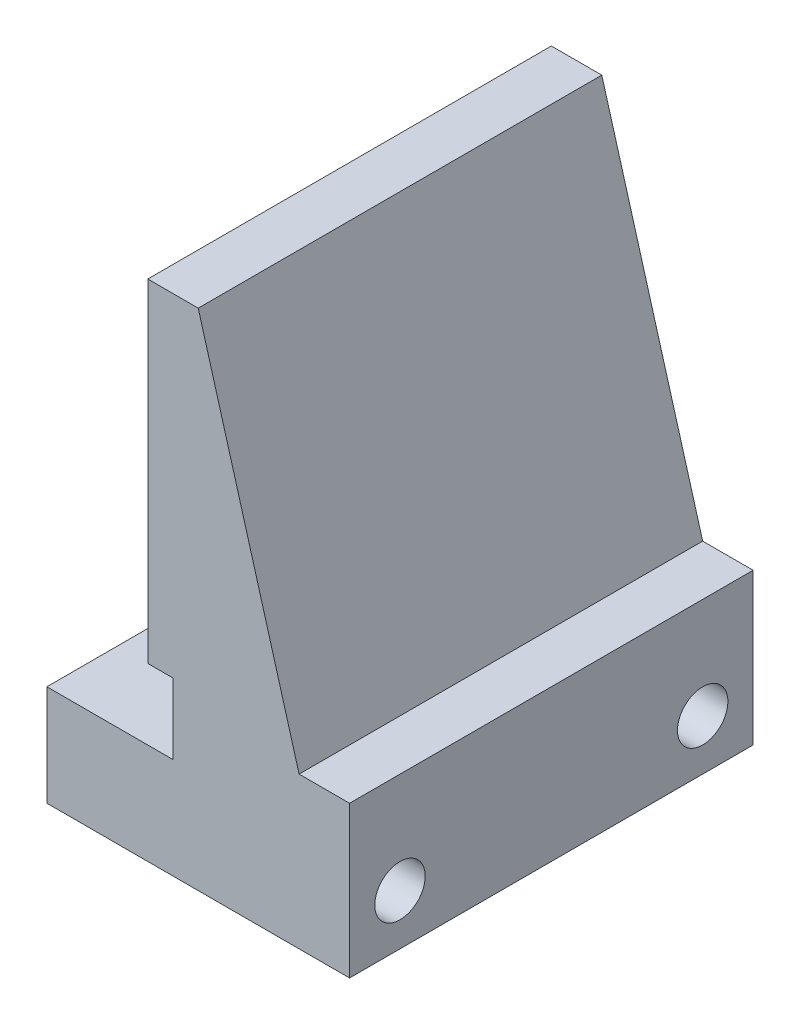
SolidWorks part; units mm, degrees
ref_plane "Front Plane" through (0, 0, 0) normal (0, 0, 1) x (1, 0, 0)
ref_plane "Top Plane" through (0, 0, 0) normal (0, 1, 0) x (1, 0, 0)
ref_plane "Right Plane" through (0, 0, 0) normal (1, 0, 0) x (0, 0, -1)
sketch "Sketch1" plane through (0, 0, 0) normal (0, 0, 1) x (1, 0, 0)
  line L0 (0, 34.6) -> (5, 34.6)
  line L3 (20, -5.4) -> (20, -0.4)
  line L4 (5, 34.6) -> (15, -0.4)
  line L5 (15, -0.4) -> (20, -0.4)
  line L6 (0, 1.6) -> (0, 34.6)
  line L8 (0, -15.4) -> (20, -15.4)
  line L9 (20, -15.4) -> (20, -5.4)
  line L10 (0, -5.4) -> (-10, -5.4)
  line L11 (-10, -5.4) -> (-10, -15.4)
  line L12 (-10, -15.4) -> (0, -15.4)
  line L13 (0, -5.4) -> (2.5, -5.4)
  line L14 (2.5, -5.4) -> (2.5, 1.6)
  line L15 (2.5, 1.6) -> (0, 1.6)
  dimension "D1" = 5
  dimension "D2" = 40
  dimension "D3" = 20
  dimension "D4" = 5
  dimension "D5" = 5
  dimension "D6" = 10
  dimension "D7" = 10
  dimension "D8" = 7
extrude "Boss-Extrude2" add sketch "Sketch1" along normal blind 40
sketch "Sketch7" plane through (20, 0, 0) normal (1, 0, 0) x (0, 0, -1)
  circle A0 centre (-35, -10.4) radius 2.5
  circle A1 centre (-5, -10.4) radius 2.5
extrude "Cut-Extrude1" cut sketch "Sketch7" against normal through all
sketch "Sketch8" plane through (0, -5.4, 0) normal (0, 1, 0) x (1, 0, 0)
  circle A0 centre (-5, -20) radius 0.75
extrude "Boss-Extrude3" add sketch "Sketch8" along normal blind 5
